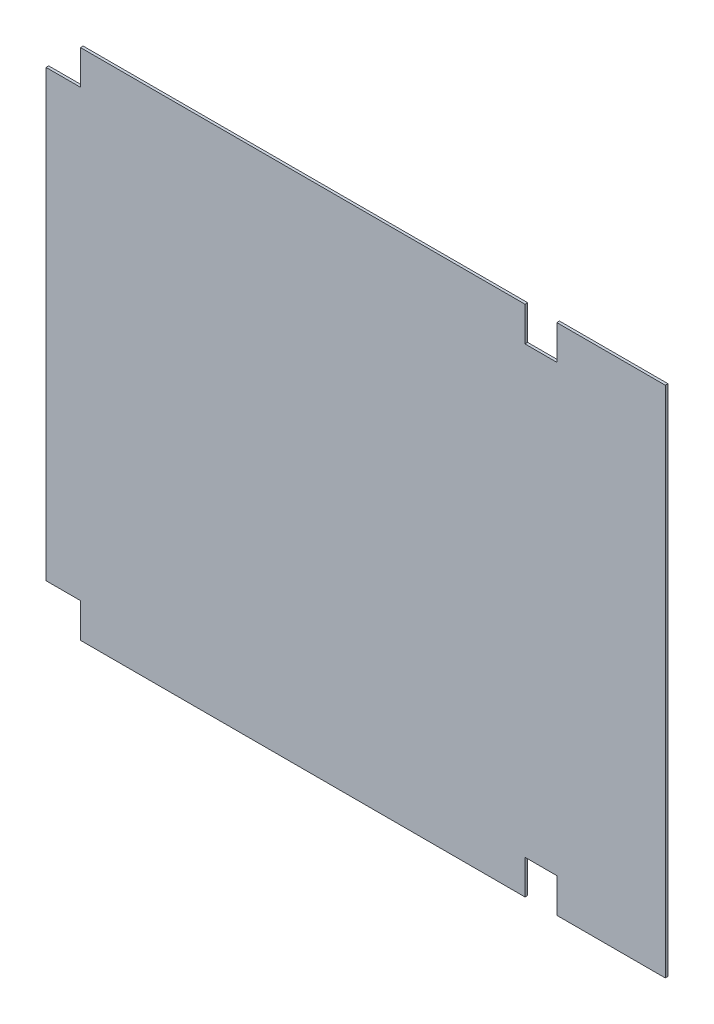
SolidWorks part; units mm, degrees
ref_plane "Front Plane" through (0, 0, 0) normal (0, 0, 1) x (1, 0, 0)
ref_plane "Top Plane" through (0, 0, 0) normal (0, 1, 0) x (1, 0, 0)
ref_plane "Right Plane" through (0, 0, 0) normal (1, 0, 0) x (0, 0, -1)
sketch "Sketch1" plane through (0, 0, 0) normal (0, 0, 1) x (1, 0, 0)
  line L1 (-371.475, -307.975) -> (371.475, -307.975)
  line L2 (-371.475, -307.975) -> (-371.475, 307.975)
  line L3 (-371.475, 307.975) -> (371.475, 307.975)
  line L4 (371.475, -307.975) -> (371.475, 307.975)
  line L5 (-371.475, -307.975) -> (371.475, 307.975) construction
  line L6 (-371.475, 307.975) -> (371.475, -307.975) construction
  point P0 (0, 0)
  dimension "D1" = 742.95
  dimension "D2" = 615.95
extrude "Boss-Extrude1" add sketch "Sketch1" along normal blind 3.175
sketch "Sketch2" plane through (0, 0, 3.175) normal (0, 0, 1) x (1, 0, 0)
  line L0 (371.475, 307.975) -> (-371.475, 307.975) construction
  line L1 (-371.475, 307.975) -> (-330.2, 307.975)
  line L2 (-371.475, 307.975) -> (-371.475, 266.7)
  line L3 (-371.475, 266.7) -> (-330.2, 266.7)
  line L4 (-330.2, 307.975) -> (-330.2, 266.7)
  line L5 (-371.475, 307.975) -> (-371.475, -307.975) construction
  line L6 (371.475, -307.975) -> (371.475, 307.975) construction
  line L7 (-371.475, -307.975) -> (-330.2, -307.975)
  line L8 (-371.475, -307.975) -> (-371.475, -266.7)
  line L9 (-371.475, -266.7) -> (-330.2, -266.7)
  line L10 (-330.2, -307.975) -> (-330.2, -266.7)
  line L11 (203.2, 307.975) -> (241.3, 307.975)
  line L12 (203.2, 307.975) -> (203.2, 266.7)
  line L13 (203.2, 266.7) -> (241.3, 266.7)
  line L14 (241.3, 307.975) -> (241.3, 266.7)
  line L15 (-371.475, -307.975) -> (371.475, -307.975) construction
  line L16 (203.2, -307.975) -> (241.3, -307.975)
  line L17 (203.2, -307.975) -> (203.2, -266.7)
  line L18 (203.2, -266.7) -> (241.3, -266.7)
  line L19 (241.3, -307.975) -> (241.3, -266.7)
  point P26 (217.9559, -216.0131)
  point P27 (196.7095, -266.7)
  dimension "D1" = 41.275
  dimension "D2" = 41.275
  dimension "D3" = 130.175
  dimension "D4" = 38.1
extrude "Cut-Extrude1" cut sketch "Sketch2" against normal through all
